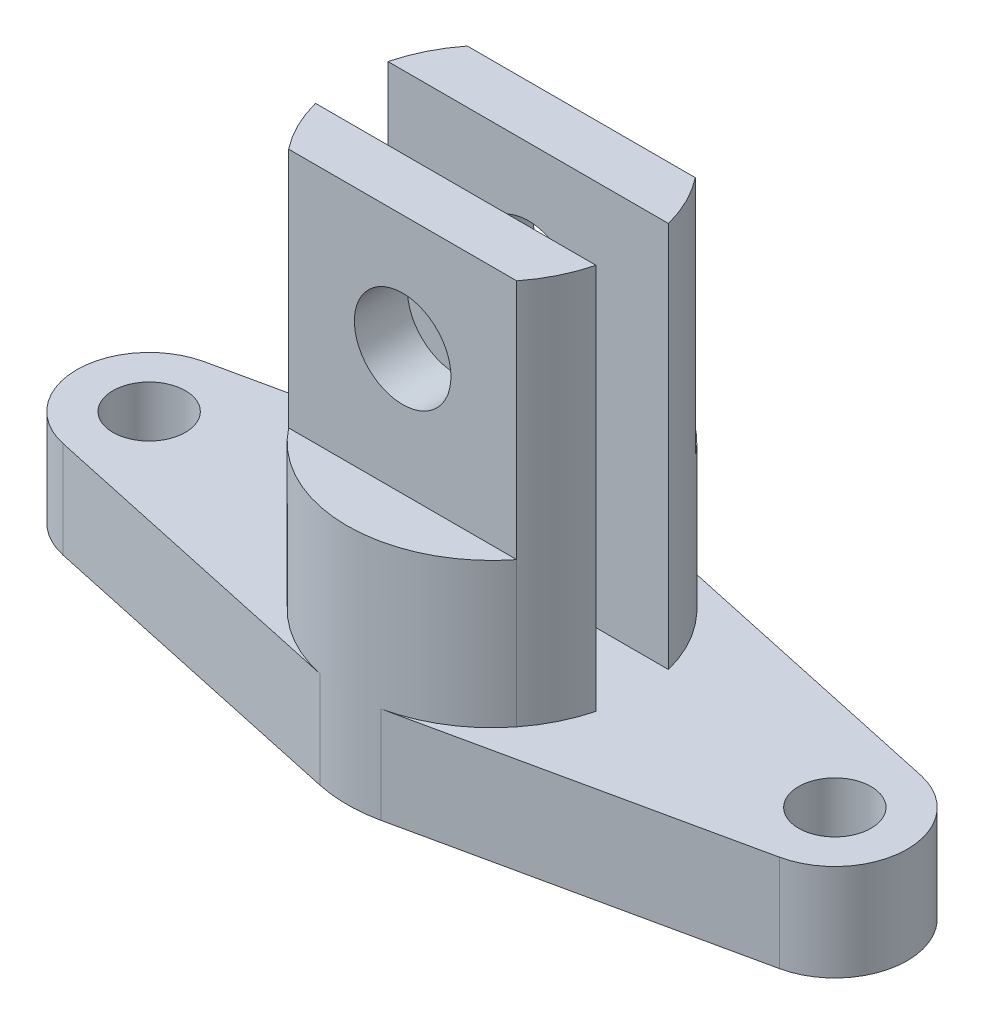
SolidWorks part; units mm, degrees
ref_plane "Alzado" through (0, 0, 0) normal (0, 0, 1) x (1, 0, 0)
ref_plane "Planta" through (0, 0, 0) normal (0, 1, 0) x (1, 0, 0)
ref_plane "Vista lateral" through (0, 0, 0) normal (1, 0, 0) x (0, 0, -1)
sketch "Croquis1" plane through (0, 0, 0) normal (0, 1, 0) x (1, 0, 0)
  line L0 (-74.169, 14.6614) -> (-6.338, 29.3228)
  line L1 (6.338, 29.3228) -> (74.169, 14.6614)
  line L2 (-74.169, -14.6614) -> (-6.338, -29.3228)
  line L3 (6.338, -29.3228) -> (74.169, -14.6614)
  line L4 (-71, 0) -> (71, 0) construction
  line L5 (0, 7.5) -> (0, -7.5) construction
  line L6 (-29.0474, 7.5) -> (29.0474, 7.5)
  line L7 (-29.0474, -7.5) -> (29.0474, -7.5)
  line L8 (0, 18.5) -> (0, -18.5) construction
  line L9 (-23.6167, 18.5) -> (23.6167, 18.5)
  line L10 (-23.6167, -18.5) -> (23.6167, -18.5)
  circle A0 centre (0, 0) radius 30
  arc A1 (74.169, -14.6614) -> (74.169, 14.6614) centre (71, 0) ccw
  circle A2 centre (-71, 0) radius 7.5
  circle A3 centre (71, 0) radius 7.5
  arc A4 (-74.169, 14.6614) -> (-74.169, -14.6614) centre (-71, 0) ccw
  point P19 (0, 0)
  point P21 (0, 0)
  point P24 (0, 7.5)
  point P27 (0, -7.5)
  point P30 (0, 0)
  point P33 (0, 18.5)
  point P36 (0, -18.5)
  dimension "D1" = 30
  dimension "D2" = 15
  dimension "D3" = 15
  dimension "D4" = 15
  dimension "D5" = 15
  dimension "D6" = 142
  dimension "D7" = 15
  dimension "D8" = 37
extrude "Saliente-Extruir2" add sketch "Croquis1" along normal blind 20 contours L3 A1 L1 A0 A3 | L10 A0 L7 | A0 L10 | L7 A0 L6 | L6 A0 L9 | L9 A0 | L0 A4 L2 A0 A2
sketch "Croquis2" plane through (0, 20, 0) normal (0, 1, 0) x (1, 0, 0)
  line L0 (0, 18.5) -> (0, -18.5) construction
  line L1 (-23.6167, 18.5) -> (23.6167, 18.5)
  line L2 (-23.6167, -18.5) -> (23.6167, -18.5)
  arc A0 (-23.6167, -18.5) -> (23.6167, -18.5) centre (0, 0) ccw
  arc A1 (23.6167, 18.5) -> (-23.6167, 18.5) centre (0, 0) ccw
  point P6 (0, 0)
  point P9 (0, 18.5)
  point P12 (0, -18.5)
  dimension "D2" = 60
  dimension "D1" = 37
extrude "Saliente-Extruir3" add sketch "Croquis2" along normal blind 30
sketch "Croquis3" plane through (0, 20, 0) normal (0, 1, 0) x (1, 0, 0)
  line L0 (0, 7.5) -> (0, -7.5) construction
  line L1 (-29.0474, 7.5) -> (29.0474, 7.5)
  line L2 (-29.0474, -7.5) -> (29.0474, -7.5)
  line L5 (-23.6167, 18.5) -> (23.6167, 18.5)
  line L6 (-23.6167, -18.5) -> (23.6167, -18.5)
  circle A0 centre (0, 0) radius 30
  arc A1 (-23.6167, 18.5) -> (-29.0474, 7.5) centre (0, 0) ccw
  arc A2 (29.0474, 7.5) -> (23.6167, 18.5) centre (0, 0) ccw
  arc A3 (29.0474, -7.5) -> (23.6167, -18.5) centre (0, 0) cw
  arc A4 (-23.6167, -18.5) -> (-29.0474, -7.5) centre (0, 0) cw
  point P6 (0, 0)
  point P9 (0, 7.5)
  point P12 (0, -7.5)
  line M17 (23.6167, 18.5) -> (-23.6167, 18.5)
  dimension "D1" = 60
  dimension "D2" = 15
extrude "Saliente-Extruir4" add sketch "Croquis3" along normal blind 80 contours L1 A0 M17 | L2 A3 L6 A4
sketch "Croquis4" plane through (0, 0, 18.5) normal (0, 0, 1) x (1, 0, 0)
  line L0 (-23.6167, 100) -> (23.6167, 100) construction
  circle A0 centre (0, 76) radius 10
  point P2 (0, 72.0422)
  dimension "D1" = 20
  dimension "D2" = 24
extrude "Cortar-Extruir1" cut sketch "Croquis4" against normal through all
